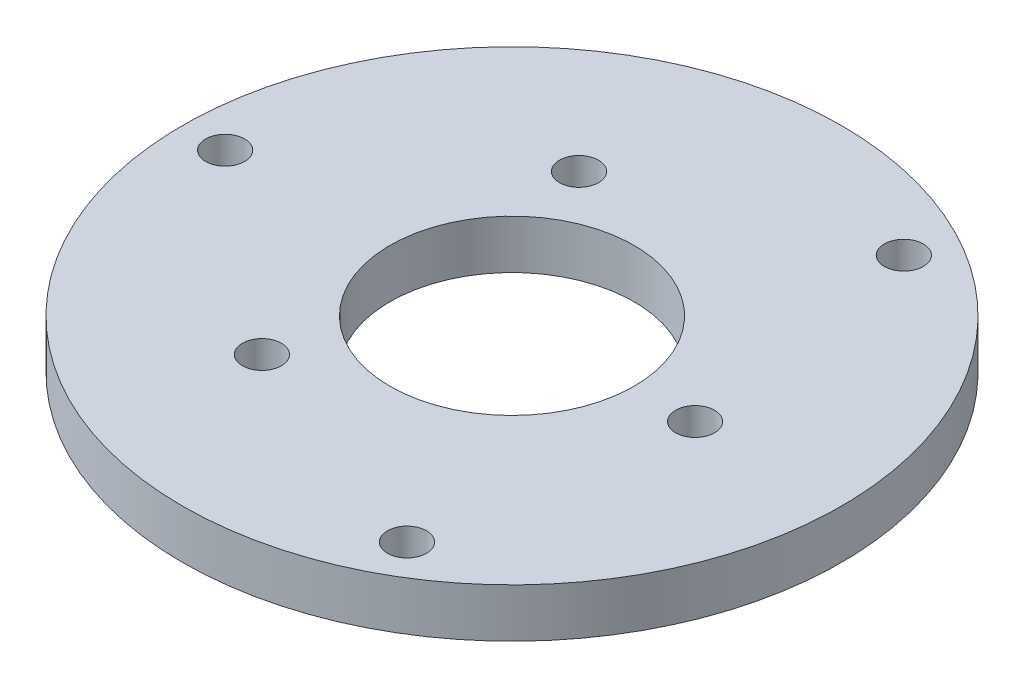
SolidWorks part; units mm, degrees
material "ABS"
ref_plane "前视基准面" through (0, 0, 0) normal (0, 0, 1) x (1, 0, 0)
ref_plane "上视基准面" through (0, 0, 0) normal (0, 1, 0) x (1, 0, 0)
ref_plane "右视基准面" through (0, 0, 0) normal (1, 0, 0) x (0, 0, -1)
sketch "草图1" plane through (0, 0, 0) normal (0, 1, 0) x (1, 0, 0)
  line L1 (15, 0) -> (-7.5, 12.9904) construction
  line L2 (-7.5, 12.9904) -> (-7.5, -12.9904) construction
  line L3 (-7.5, -12.9904) -> (15, 0) construction
  circle A0 centre (0, 0) radius 10
  circle A1 centre (0, 0) radius 20 construction
  circle A2 centre (0, 0) radius 15 construction
  circle A3 centre (15, 0) radius 1.6
  circle A4 centre (-7.5, -12.9904) radius 1.6
  circle A5 centre (-7.5, 12.9904) radius 1.6
  circle A6 centre (0, 0) radius 27
  dimension "D1" = 20
  dimension "D2" = 40
  dimension "D3" = 30
  dimension "D4" = 3.2
  dimension "D5" = 3.2
  dimension "D6" = 3.2
  dimension "D7" = 54
extrude "凸台-拉伸1" add sketch "草图1" along normal blind 4
sketch "草图2" plane through (0, 4, 0) normal (0, 1, 0) x (1, 0, 0)
  line L1 (-23.5, 0) -> (11.75, -20.3516) construction
  line L2 (11.75, -20.3516) -> (11.75, 20.3516) construction
  line L3 (11.75, 20.3516) -> (-23.5, 0) construction
  circle A0 centre (0, 0) radius 23.5 construction
  circle A1 centre (11.75, -20.3516) radius 3.5 construction
  circle A2 centre (-23.5, 0) radius 3.5 construction
  circle A3 centre (11.75, 20.3516) radius 3.5 construction
  circle A4 centre (0, 0) radius 20 construction
  dimension "D1" = 7
  dimension "D2" = 7
  dimension "D3" = 7
  dimension "D4" = 40
sketch "草图3" plane through (0, 4, 0) normal (0, 1, 0) x (1, 0, 0)
  circle A0 centre (11.75, 20.3516) radius 1.6
  circle A1 centre (11.75, -20.3516) radius 1.6
  circle A2 centre (-23.5, 0) radius 1.6
  dimension "D1" = 3.2
  dimension "D2" = 3.2
extrude "切除-拉伸1" cut sketch "草图3" against normal blind 10
